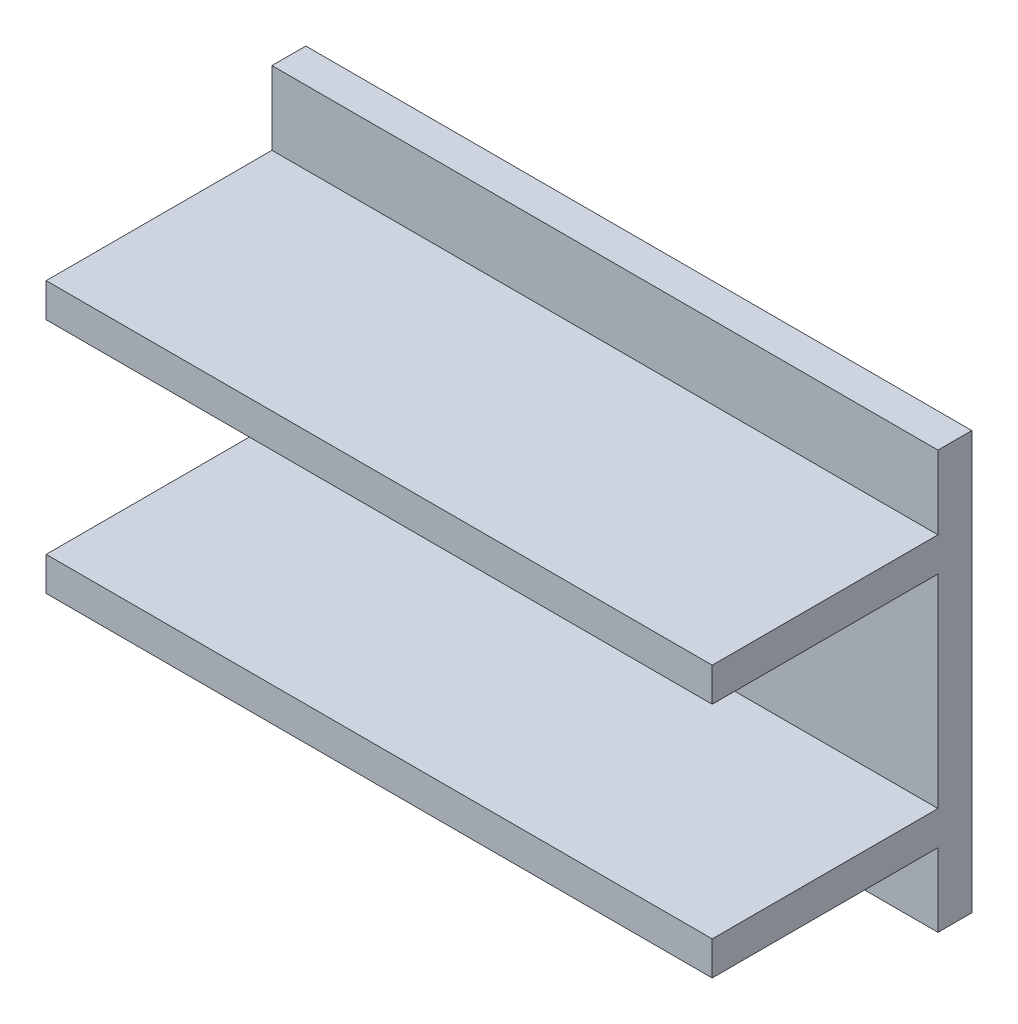
SolidWorks part; units mm, degrees
ref_plane "前视基准面" through (0, 0, 0) normal (0, 0, 1) x (1, 0, 0)
ref_plane "上视基准面" through (0, 0, 0) normal (0, 1, 0) x (1, 0, 0)
ref_plane "右视基准面" through (0, 0, 0) normal (1, 0, 0) x (0, 0, -1)
other "Configuration Table"
sketch "草图1" plane through (0, 0, 0) normal (0, 0, 1) x (1, 0, 0)
  line L1 (-29.5, -18.5) -> (29.5, -18.5)
  line L2 (-29.5, -18.5) -> (-29.5, 18.5)
  line L3 (-29.5, 18.5) -> (29.5, 18.5)
  line L4 (29.5, -18.5) -> (29.5, 18.5)
  line L5 (-29.5, -18.5) -> (29.5, 18.5) construction
  line L6 (-29.5, 18.5) -> (29.5, -18.5) construction
  point P0 (0, 0)
  dimension "D1" = 59
  dimension "D2" = 37
extrude "凸台-拉伸1" add sketch "草图1" along normal blind 3
sketch "草图2" plane through (0, 0, 3) normal (0, 0, 1) x (1, 0, 0)
  line L12 (-29.5, 18.5) -> (-29.5, -18.5) construction
  line L13 (-29.5, -12) -> (29.5, -12)
  line L14 (-29.5, -12) -> (-29.5, -9)
  line L15 (-29.5, -9) -> (29.5, -9)
  line L16 (29.5, -12) -> (29.5, -9)
  line L17 (29.5, -18.5) -> (29.5, 18.5) construction
  line L18 (-29.5, -18.5) -> (29.5, -18.5) construction
  line L19 (29.5, 12) -> (-29.5, 12)
  line L20 (29.5, 12) -> (29.5, 9)
  line L21 (29.5, 9) -> (-29.5, 9)
  line L22 (-29.5, 12) -> (-29.5, 9)
  line L23 (29.5, 18.5) -> (-29.5, 18.5) construction
  dimension "D1" = 6.5
  dimension "D2" = 6.5
  dimension "D3" = 3
  dimension "D4" = 3
extrude "凸台-拉伸2" add sketch "草图2" along normal blind 20
